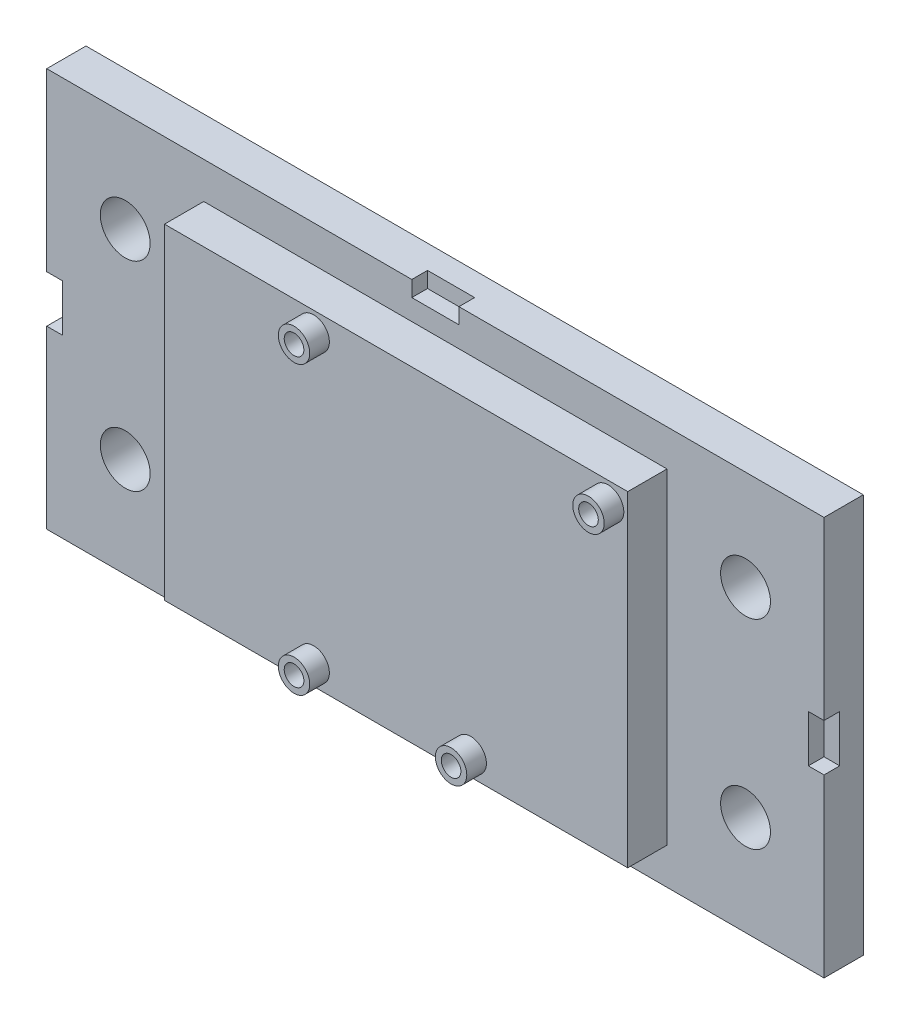
SolidWorks part; units mm, degrees
ref_plane "Front Plane" through (0, 0, 0) normal (0, 0, 1) x (1, 0, 0)
ref_plane "Top Plane" through (0, 0, 0) normal (0, 1, 0) x (1, 0, 0)
ref_plane "Right Plane" through (0, 0, 0) normal (1, 0, 0) x (0, 0, -1)
sketch "Sketch1" plane through (0, 0, 0) normal (0, 0, 1) x (1, 0, 0)
  line L1 (-49.5, 25.4) -> (49.5, 25.4)
  line L2 (-49.5, 25.4) -> (-49.5, -25.4)
  line L3 (-49.5, -25.4) -> (49.5, -25.4)
  line L4 (49.5, 25.4) -> (49.5, -25.4)
  point P0 (0, 0)
  dimension "D1" = 50.8
  dimension "D2" = 49.5
  dimension "D3" = 49.5
  dimension "D4" = 25.4
extrude "Boss-Extrude1" add sketch "Sketch1" along normal blind 5
sketch "Sketch3" plane through (0, 0, 5) normal (0, 0, 1) x (1, 0, 0)
  line L1 (29.5, 20.75) -> (-29.5, 20.75)
  line L2 (29.5, 20.75) -> (29.5, -20.75)
  line L3 (29.5, -20.75) -> (-29.5, -20.75)
  line L4 (-29.5, 20.75) -> (-29.5, -20.75)
  line L5 (29.5, 20.75) -> (-29.5, -20.75) construction
  line L6 (29.5, -20.75) -> (-29.5, 20.75) construction
  point P0 (0, 0)
  dimension "D1" = 59
  dimension "D2" = 41.5
extrude "Boss-Extrude2" add sketch "Sketch3" along normal blind 5
sketch "Sketch2" plane through (0, 0, 5) normal (0, 0, 1) x (1, 0, 0)
  line L0 (49.5, 25.4) -> (-49.5, 25.4) construction
  line L1 (-49.5, -25.4) -> (49.5, -25.4) construction
  line L2 (-49.5, 25.4) -> (-49.5, -25.4) construction
  line L3 (49.5, -25.4) -> (49.5, 25.4) construction
  circle A0 centre (-39.5, 12.7) radius 3.175
  circle A1 centre (-39.5, -12.7) radius 3.175
  circle A2 centre (39.5, -12.7) radius 3.175
  circle A3 centre (39.5, 12.7) radius 3.175
  dimension "D1" = 25.4
  dimension "D2" = 25.4
  dimension "D3" = 12.7
  dimension "D4" = 12.7
  dimension "D5" = 12.7
  dimension "D6" = 12.7
  dimension "D7" = 10
  dimension "D8" = 10
extrude "Cut-Extrude1" cut sketch "Sketch2" against normal through all
sketch "Sketch4" plane through (0, 0, 10) normal (0, 0, 1) x (1, 0, 0)
  circle A0 centre (-10.5, -18.25) radius 2
  circle A1 centre (9.5, -18.25) radius 2
  circle A2 centre (-10.5, 18.25) radius 2
  circle A3 centre (27, 18.25) radius 2
  dimension "D1" = 4
  dimension "D2" = 4
  dimension "D3" = 4
  dimension "D4" = 4
  dimension "D5" = 19
  dimension "D6" = 2.5
  dimension "D7" = 2.5
  dimension "D8" = 39
  dimension "D9" = 19
  dimension "D10" = 39
  dimension "D11" = 39
  dimension "D12" = 56.5
extrude "Boss-Extrude3" add sketch "Sketch4" along normal blind 2.5
sketch "Sketch5" plane through (0, 0, 12.5) normal (0, 0, 1) x (1, 0, 0)
  circle A0 centre (-10.5, 18.25) radius 1.25
  circle A1 centre (27, 18.25) radius 1.25
  circle A2 centre (9.5, -18.25) radius 1.25
  circle A3 centre (-10.5, -18.25) radius 1.25
  circle A4 centre (-10.5, -18.25) radius 2 construction
  circle A5 centre (9.5, -18.25) radius 2 construction
  circle A6 centre (27, 18.25) radius 2 construction
  circle A7 centre (-10.5, 18.25) radius 2 construction
extrude "Cut-Extrude2" cut sketch "Sketch5" against normal blind 12
sketch "Sketch6" plane through (0, -25.4, 0) normal (0, -1, 0) x (-1, 0, 0)
  line L0 (3, -3) -> (-3, -3)
  line L1 (-3, -3) -> (-3, -5)
  line L2 (49.5, -5) -> (-49.5, -5) construction
  line L3 (-3, -5) -> (3, -5)
  line L4 (29.5, -5) -> (-29.5, -5) construction
  line L5 (3, -5) -> (3, -3)
  point P3 (0, -3)
  dimension "D1" = 6
  dimension "D2" = 2
extrude "Cut-Extrude3" cut sketch "Sketch6" against normal blind 2
sketch "Sketch7" plane through (-49.5, 0, 0) normal (-1, 0, 0) x (0, 0, 1)
  line L0 (3, 3) -> (3, -3)
  line L1 (3, -3) -> (5, -3)
  line L2 (5, 25.4) -> (5, -25.4) construction
  line L3 (5, -3) -> (5, 3)
  line L4 (5, 20.75) -> (5, -20.75) construction
  line L5 (5, 3) -> (3, 3)
  point P3 (3, 0)
  dimension "D1" = 2
  dimension "D2" = 6
extrude "Cut-Extrude4" cut sketch "Sketch7" against normal blind 2
mirror "Mirror1" about plane through (0, 0, 0) normal (0, 1, 0) of "Cut-Extrude3"
mirror "Mirror2" about plane through (0, 0, 0) normal (1, 0, 0) of "Cut-Extrude4"
